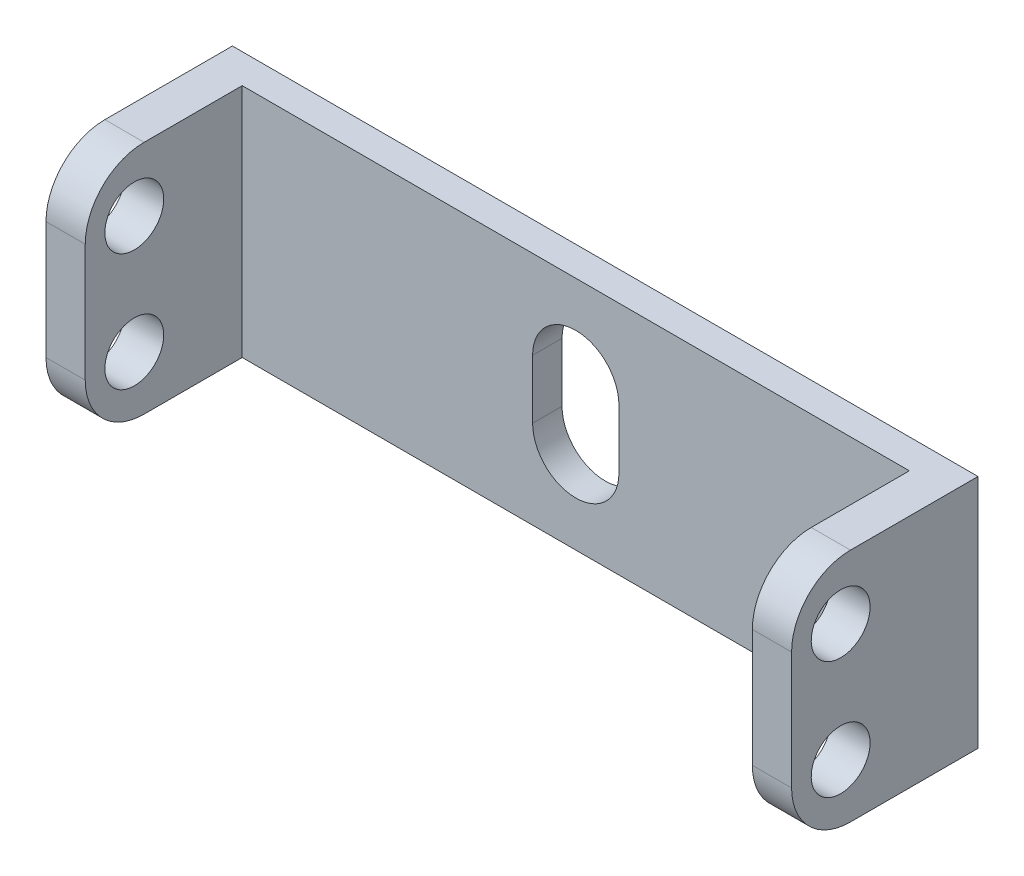
SolidWorks part; units mm, degrees
ref_plane "Front" through (0, 0, 0) normal (0, 0, 1) x (1, 0, 0)
ref_plane "Top" through (0, 0, 0) normal (0, 1, 0) x (1, 0, 0)
ref_plane "Right" through (0, 0, 0) normal (1, 0, 0) x (0, 0, -1)
sketch "Sketch1" plane through (0, 0, 0) normal (0, 0, 1) x (1, 0, 0)
  line L1 (-19, 6) -> (19, 6)
  line L2 (-19, 6) -> (-19, -6)
  line L3 (-19, -6) -> (19, -6)
  line L4 (19, 6) -> (19, -6)
  dimension "D1" = 12
  dimension "D2" = 38
  dimension "D3" = 6
  dimension "D4" = 19
extrude "Extrude1" add sketch "Sketch1" along normal blind 1.5
sketch "Sketch2" plane through (0, 0, 1.5) normal (0, 0, 1) x (1, 0, 0)
  line L0 (-19, -6) -> (19, -6) construction
  line L1 (-19, 6) -> (-17, 6)
  line L2 (-19, 6) -> (-19, -6)
  line L3 (-19, -6) -> (-17, -6)
  line L4 (-17, 6) -> (-17, -6)
  line L6 (19, 6) -> (17, 6)
  line L7 (19, 6) -> (19, -6)
  line L8 (19, -6) -> (17, -6)
  line L9 (17, 6) -> (17, -6)
  dimension "D1" = 2
  dimension "D2" = 2
extrude "Extrude2" add sketch "Sketch2" along normal blind 8
sketch "Sketch3" plane through (19, 0, 0) normal (1, 0, 0) x (0, 0, -1)
  line L0 (-9.5, -6) -> (-9.5, 6) construction
  line L1 (-9.5, 6) -> (0, 6) construction
  line L2 (-9.5, -6) -> (0, -6) construction
  circle A0 centre (-7, 3) radius 1.5
  circle A1 centre (-7, -3) radius 1.5
  dimension "D1" = 3
  dimension "D2" = 3
  dimension "D3" = 2.5
  dimension "D4" = 2.5
  dimension "D5" = 3
  dimension "D6" = 3
extrude "Extrude3" cut sketch "Sketch3" against normal up to surface (38 mm away) up to face at (-19, 0, 4.75)
fillet "Fillet1" radius 3 4 edges at (18, 6, 9.5) (18, -6, 9.5) (-18, -6, 9.5) (-18, 6, 9.5)
sketch "Sketch4" plane through (0, 0, 1.5) normal (0, 0, 1) x (1, 0, 0)
  line L0 (-2.2, 1.5) -> (-2.2, -1.5)
  line L1 (2.2, 1.5) -> (2.2, -1.5)
  arc A0 (2.2, 1.5) -> (-2.2, 1.5) centre (0, 1.5) ccw
  arc A1 (2.2, -1.5) -> (-2.2, -1.5) centre (0, -1.5) cw
  dimension "D7" = 2.2
  dimension "D8" = 2.2
  dimension "D1" = 2.2
  dimension "D2" = 2.2
  dimension "D3" = 3
  dimension "D4" = 3
  dimension "D5" = 1.5
  dimension "D6" = 1.5
extrude "Extrude4" cut sketch "Sketch4" against normal up to surface (1.5 mm away) up to face at (0, 0, 0)
